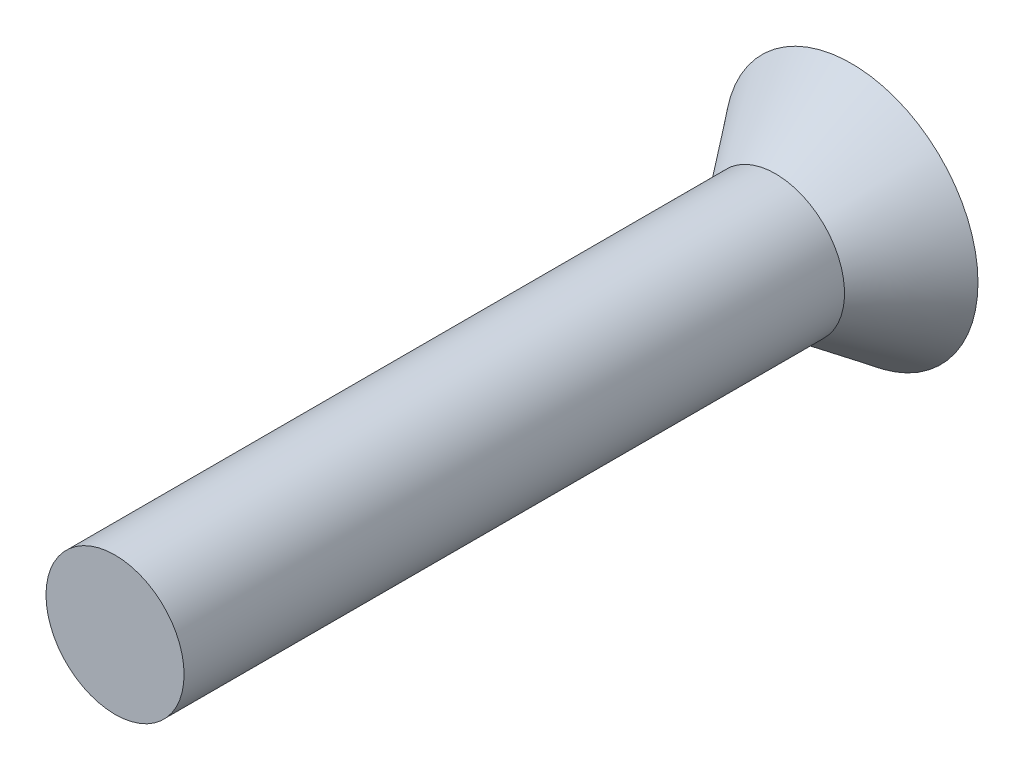
SolidWorks part; units mm, degrees
ref_plane "前视基准面" through (0, 0, 0) normal (0, 0, 1) x (1, 0, 0)
ref_plane "上视基准面" through (0, 0, 0) normal (0, 1, 0) x (1, 0, 0)
ref_plane "右视基准面" through (0, 0, 0) normal (1, 0, 0) x (0, 0, -1)
sketch "草图1" plane through (0, 0, 0) normal (0, 0, 1) x (1, 0, 0)
  circle A0 centre (0, 0) radius 1.5
extrude "凸台-拉伸1" add sketch "草图1" along normal blind 16
sketch "草图2" plane through (0, 0, 0) normal (0, 1, 0) x (1, 0, 0)
  line L0 (1.5, 0) -> (2.75, 0)
  line L1 (1.5, 0) -> (1.5, -1.65)
  line L3 (1.5, -16) -> (1.5, 0) construction
  line L4 (1.5, -1.65) -> (2.75, 0)
  line L5 (0, 0) -> (0, -0.7282) construction
revolve "旋转1" add sketch "草图2" angle 360 about L5
